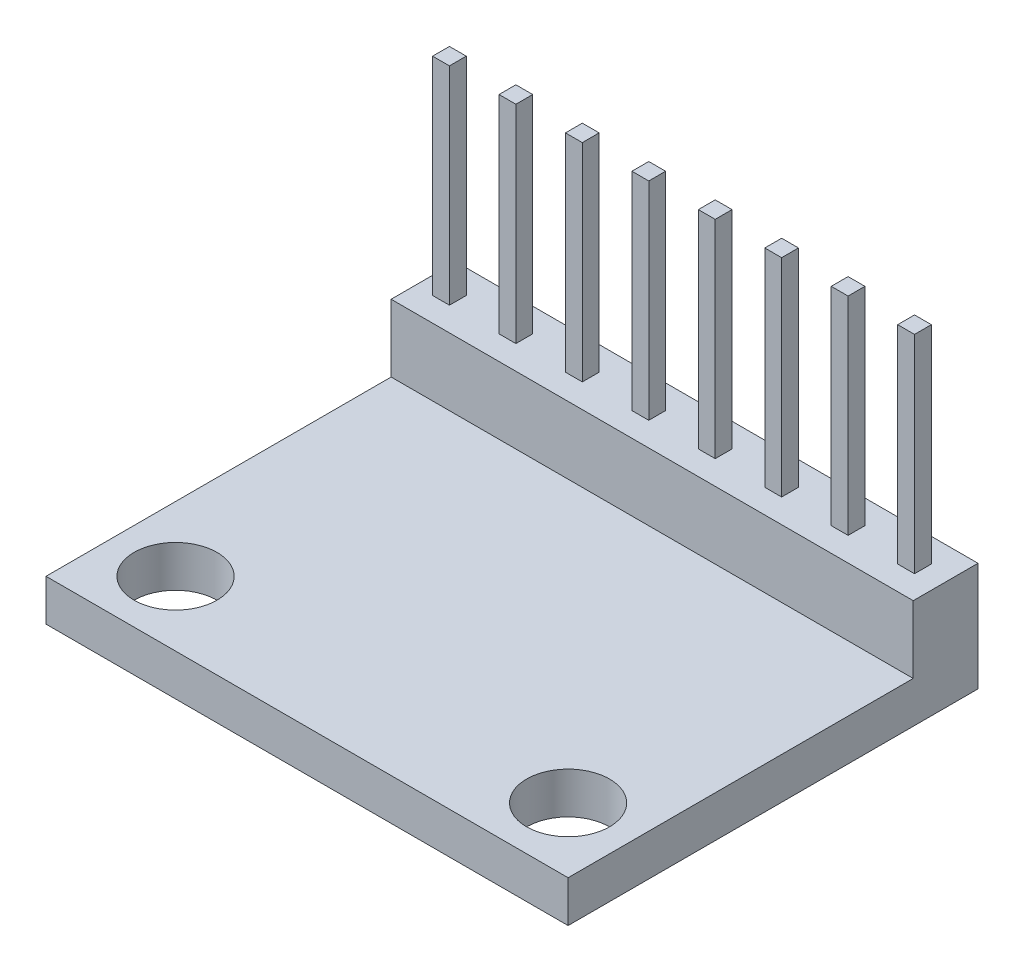
SolidWorks part; units mm, degrees
ref_plane "Front Plane" through (0, 0, 0) normal (0, 0, 1) x (1, 0, 0)
ref_plane "Top Plane" through (0, 0, 0) normal (0, 1, 0) x (1, 0, 0)
ref_plane "Right Plane" through (0, 0, 0) normal (1, 0, 0) x (0, 0, -1)
sketch "Sketch1" plane through (0, 0, 0) normal (0, 1, 0) x (1, 0, 0)
  line L1 (-10.075, -7.91) -> (10.075, -7.91)
  line L2 (-10.075, -7.91) -> (-10.075, 7.91)
  line L3 (-10.075, 7.91) -> (10.075, 7.91)
  line L4 (10.075, -7.91) -> (10.075, 7.91)
  line L5 (-10.075, -7.91) -> (10.075, 7.91) construction
  line L6 (-10.075, 7.91) -> (10.075, -7.91) construction
  point P0 (0, 0)
  dimension "D1" = 20.15
  dimension "D2" = 15.82
extrude "Boss-Extrude1" add sketch "Sketch1" along normal blind 1.6
sketch "Sketch2" plane through (0, 1.6, 0) normal (0, 1, 0) x (1, 0, 0)
  line L0 (10.075, -7.91) -> (10.075, 7.91) construction
  line L1 (-10.075, -7.91) -> (10.075, -7.91) construction
  line L2 (-10.075, 7.91) -> (-10.075, -7.91) construction
  circle A0 centre (-7.575, -5.41) radius 1.6
  circle A1 centre (7.575, -5.41) radius 1.6
  point P8 (0, 0)
  dimension "D1" = 3.2
  dimension "D2" = 2.5
  dimension "D3" = 2.5
  dimension "D4" = 2.5
extrude "Cut-Extrude1" cut sketch "Sketch2" against normal through all
sketch "Sketch3" plane through (0, 1.6, 0) normal (0, 1, 0) x (1, 0, 0)
  line L0 (10.075, -7.91) -> (10.075, 7.91) construction
  line L1 (-10.075, 7.91) -> (10.075, 7.91)
  line L2 (-10.075, 7.91) -> (-10.075, 5.41)
  line L3 (-10.075, 5.41) -> (10.075, 5.41)
  line L4 (10.075, 7.91) -> (10.075, 5.41)
  dimension "D1" = 2.5
extrude "Boss-Extrude2" add sketch "Sketch3" along normal blind 4.2 from surface at -1.6 starting at face at (-7.575, 0, 7.01)
sketch "Sketch5" plane through (0, 4.2, 0) normal (0, 1, 0) x (1, 0, 0)
  line L0 (-10.075, 5.41) -> (-10.075, 7.91) construction
  line L1 (-9.4, 6.335) -> (-8.75, 6.335)
  line L2 (-9.4, 6.335) -> (-9.4, 6.985)
  line L3 (-9.4, 6.985) -> (-8.75, 6.985)
  line L4 (-8.75, 6.335) -> (-8.75, 6.985)
  line L5 (-9.4, 6.335) -> (-8.75, 6.985) construction
  line L6 (-9.4, 6.985) -> (-8.75, 6.335) construction
  point P0 (-9.075, 6.66)
  point P5 (0, 0)
  point P8 (-10.075, 6.66)
  dimension "D1" = 0.65
  dimension "D2" = 1
extrude "Boss-Extrude3" add sketch "Sketch5" along normal blind 8
pattern_linear "LPattern1" count 8 spacing 2.5643 along (1, 0, 0) of "Boss-Extrude3"
equation "\"D2@Sketch2\"= 0.9 + \"D1@Sketch2\"/2"
